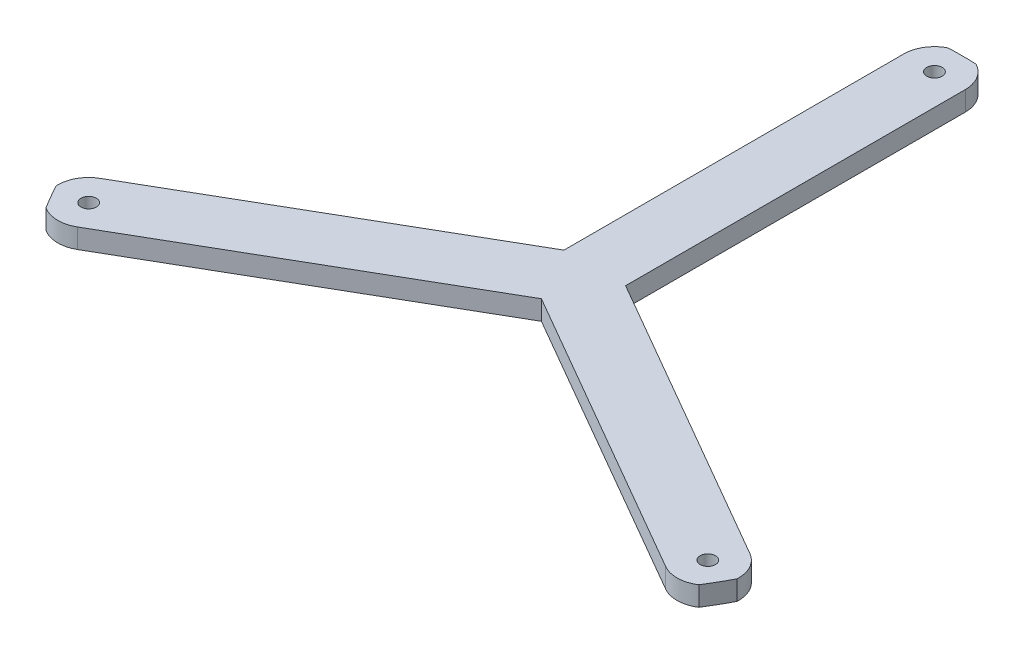
SolidWorks part; units mm, degrees
ref_plane "Front Plane" through (0, 0, 0) normal (0, 0, 1) x (1, 0, 0)
ref_plane "Top Plane" through (0, 0, 0) normal (0, 1, 0) x (1, 0, 0)
ref_plane "Right Plane" through (0, 0, 0) normal (1, 0, 0) x (0, 0, -1)
sketch "Sketch1" plane through (0, 0, 0) normal (0, 1, 0) x (1, 0, 0)
  circle A0 centre (0, 0) radius 125
  circle A1 centre (0, 116) radius 2.5
  dimension "D1" = 250
  dimension "D2" = 5
  dimension "D3" = 9
extrude "Boss-Extrude1" add sketch "Sketch1" along normal blind 6.35 contours A0
sketch "Sketch2" plane through (0, 6.35, 0) normal (0, 1, 0) x (1, 0, 0)
  line L0 (0, 0) -> (0, 125) construction
  line L1 (0, 0) -> (108.2532, -62.5) construction
  line L2 (0, 0) -> (-108.2532, -62.5) construction
  line L3 (0, 0) -> (0, 125) construction
  line L4 (0, 0) -> (108.2532, -62.5) construction
  circle A0 centre (0, 0) radius 125 construction
  circle A1 centre (0, 116) radius 2.5
  circle A2 centre (100.4589, -58) radius 2.5
  circle A3 centre (-100.4589, -58) radius 2.5
  dimension "D3" = 5
  dimension "D2" = 120
  dimension "D4" = 9
  dimension "D1" = 3
ref_plane "Plane1" through (0, 13.35, 0) normal (0, 1, 0) x (1, 0, 0)
sketch "Sketch3" plane through (0, 13.35, 0) normal (0, 1, 0) x (1, 0, 0)
  circle A0 centre (100.4589, -58) radius 2.5 construction
  circle A1 centre (0, 116) radius 2.5 construction
  circle A2 centre (-100.4589, -58) radius 2.5 construction
  point P0 (0, 116)
  point P1 (100.4589, -58)
  point P3 (-100.4589, -58)
extrude "Cut-Extrude1" cut sketch "Sketch2" against normal through all
sketch "Sketch4" plane through (0, 0, 0) normal (0, -1, 0) x (1, 0, 0)
  line L4 (0, -5) -> (0, 5)
  line L12 (-15, 0) -> (15, 0) construction
  line L13 (-35, 10) -> (-15, 10) construction
  line L14 (-15, 20) -> (-20, 20) construction
  line L15 (-25, 0) -> (-20, 0)
  line L16 (-20, 20) -> (-25, 20)
  line L17 (-15, 20) -> (-15, -20)
  line L18 (35, -20) -> (15, -20) construction
  line L19 (5, 0) -> (-5, 0)
  line L20 (15, 20) -> (15, -20)
  line L21 (25, 5) -> (15, 20)
  line L22 (35, 20) -> (25, 5)
  line L23 (35, -20) -> (35, 20)
  arc A1 (-25, 20) -> (-25, 0) centre (-25, 10) ccw
  point P21 (0, 0)
  dimension "D1" = 10
  dimension "D3" = 30
extrude "Cut-Extrude-Thin1" [suppressed] cut sketch "Sketch4" against normal blind 1 thin
sketch "Sketch6" plane through (0, 6.35, 0) normal (0, 1, 0) x (1, 0, 0)
  line L0 (0, 116) -> (0, 0) construction
  line L1 (10, 116) -> (10, 0)
  line L2 (-10, 116) -> (-10, 0)
  line L3 (0, 0) -> (100.4589, -58) construction
  line L4 (5, 8.6603) -> (105.4589, -49.3397)
  line L5 (-5, -8.6603) -> (95.4589, -66.6603)
  line L6 (0, 0) -> (-100.4589, -58) construction
  line L7 (5, -8.6603) -> (-95.4589, -66.6603)
  line L8 (-5, 8.6603) -> (-105.4589, -49.3397)
  arc A0 (10, 116) -> (-10, 116) centre (0, 116) ccw
  arc A1 (-10, 0) -> (10, 0) centre (0, 0) ccw
  arc A2 (5, 8.6603) -> (-5, -8.6603) centre (0, 0) ccw
  arc A3 (95.4589, -66.6603) -> (105.4589, -49.3397) centre (100.4589, -58) ccw
  arc A4 (5, -8.6603) -> (-5, 8.6603) centre (0, 0) ccw
  arc A5 (-105.4589, -49.3397) -> (-95.4589, -66.6603) centre (-100.4589, -58) ccw
  circle A6 centre (0, 0) radius 125 construction
  circle A7 centre (100.4589, -58) radius 2.5 construction
  circle A8 centre (-100.4589, -58) radius 2.5 construction
  circle A9 centre (0, 116) radius 2.5 construction
  circle A10 centre (0, 0) radius 125
  circle A11 centre (100.4589, -58) radius 2.5
  circle A12 centre (-100.4589, -58) radius 2.5
  circle A13 centre (0, 116) radius 2.5
  point P4 (0, 58)
  point P9 (50.2295, -29)
  point P17 (-50.2295, -29)
  point P37 (0, 0)
  circle M16 centre (0, 0) radius 125
  dimension "D1" = 10
extrude "Cut-Extrude2" cut sketch "Sketch6" against normal blind 10 contours A5 L8 L2 A0 M16 | A3 A0 L1 L4 M16 | A5 A3 L5 L7 M16
